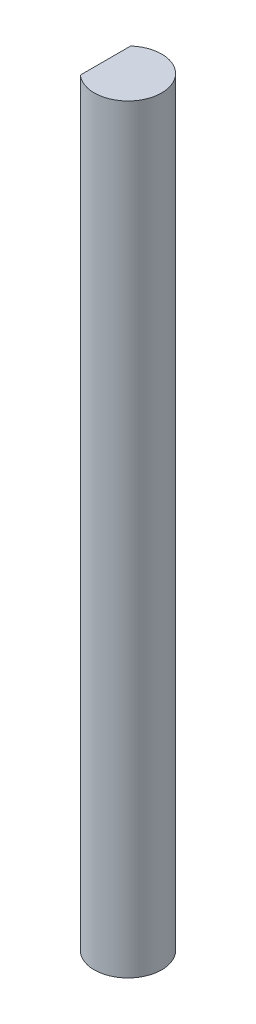
SolidWorks part; units mm, degrees
other "标注1"
sketch "草图3" plane through (-22.25, 4, -10) normal (-0.231, 0.6469, -0.7268) x (-0.9696, -0.2151, 0.1167)
ref_plane "前视基准面" through (0, 0, 0) normal (0, 0, 1) x (1, 0, 0)
ref_plane "上视基准面" through (0, 0, 0) normal (0, 1, 0) x (1, 0, 0)
ref_plane "右视基准面" through (0, 0, 0) normal (1, 0, 0) x (0, 0, -1)
other "Configuration Table"
sketch "草图4" plane through (0, 0, 0) normal (0, 1, 0) x (1, 0, 0)
  line L0 (-1, 1.118) -> (-1, -1.118)
  circle A1 centre (0, 0) radius 1.5
  dimension "D1" = 1
  dimension "D2" = 3
extrude "凸台-拉伸1" add sketch "草图4" along normal blind 33.8 contours L0 A1
